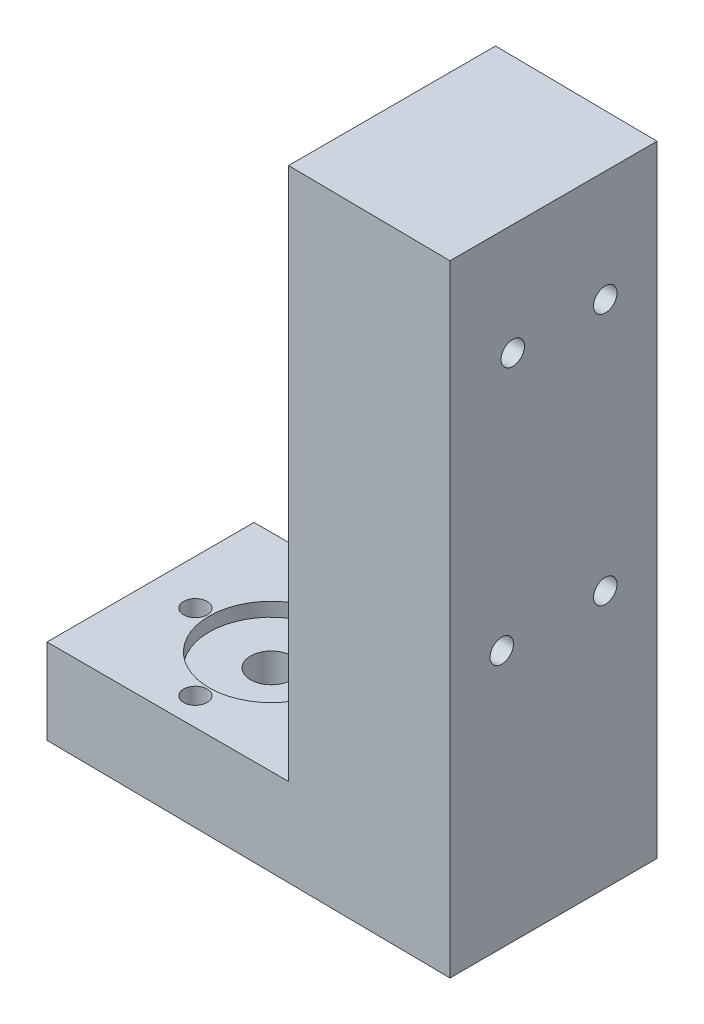
SolidWorks part; units mm, degrees
ref_plane "Front Plane" through (0, 0, 0) normal (0, 0, 1) x (1, 0, 0)
ref_plane "Top Plane" through (0, 0, 0) normal (0, 1, 0) x (1, 0, 0)
ref_plane "Right Plane" through (0, 0, 0) normal (1, 0, 0) x (0, 0, -1)
sketch "Sketch1" plane through (0, 0, 0) normal (0, 0, 1) x (1, 0, 0)
  line L0 (0, 0) -> (58.3993, -0.6295)
  line L1 (58.3993, -0.6295) -> (58.3993, 89.3705)
  line L2 (58.3993, 89.3705) -> (35, 89.6228)
  line L3 (35, 89.6228) -> (35, 12.3346)
  line L4 (35, 12.3346) -> (0, 12.3346)
  line L5 (0, 12.3346) -> (0, 0)
  dimension "D1" = 12.3346
  dimension "D3" = 35
  dimension "D2" = 23.3993
  dimension "D4" = 90
extrude "Boss-Extrude1" add sketch "Sketch1" along normal blind 30
ref_point "Point1"
sketch "Sketch2" plane through (0, 12.3346, 0) normal (0, 1, 0) x (1, 0, 0)
  circle A0 centre (17.5, -15) radius 3
  circle A1 centre (17.5, -15) radius 11
  circle A2 centre (6.5, -15) radius 1.7
  circle A3 centre (17.5, -4) radius 1.7
  circle A4 centre (28.5, -15) radius 1.7
  circle A5 centre (17.5, -26) radius 1.7
extrude "Cut-Extrude1" cut sketch "Sketch2" against normal up to next contours A4 | A3 | A2 | A0 | A5
sketch "Sketch3" plane through (0, 12.3346, 0) normal (0, 1, 0) x (1, 0, 0)
  circle A0 centre (17.5, -15) radius 9
extrude "Cut-Extrude2" cut sketch "Sketch3" against normal blind 2
sketch "Sketch4" plane through (35, 0, 0) normal (-1, 0, 0) x (0, 0, 1)
  line L0 (30, -0.6295) -> (0, -0.6295) construction
  line L1 (30, 89.6228) -> (30, 12.3346) construction
  line L2 (0, 89.6228) -> (0, 12.3346) construction
  circle A0 centre (22.5, 36.7005) radius 1.7
  circle A1 centre (7.5, 36.7005) radius 1.7
  circle A2 centre (7.5, 73.2705) radius 1.7
  circle A3 centre (20.9053, 73.2705) radius 1.7
  point P14 (0, 0)
  point P17 (0, 0)
  dimension "D1" = 37.33
  dimension "D2" = 7.5
  dimension "D3" = 7.5
  dimension "D4" = 73.9
extrude "Cut-Extrude3" cut sketch "Sketch4" against normal up to next
equation "\"b\" = 30'Base"
equation "\"L_1\"= 35'Feature 1 Length"
equation "\"L_2\"= 18'Motor Shaft Length"
equation "\"Yield\"= 45.2'PLA Yield Strength"
equation "\"allow\" = \"Yield\" / \"SF\"'Allowable Stress"
equation "\"SF\"= 3'Safety Factor"
equation "\"E\" = 2.35 * ( 10 ^ 6 )'PLA Modulus of Elasticity"
equation "\"P\"= 300'Force"
equation "\"M_1\" = \"P\" * \"L_2\"'Feature 1 Moment"
equation "\"h_1\"= ( ( ( 6 * \"M_1\" * ( \"L_1\" ^ 2 ) ) / ( ( \"E\" ) * ( \"b\" ) * \"def\" ) ) ) ^ ( 1 / 3 )'Feature 1 Height"
equation "\"def\"= 0.0003'Given Max Deflection"
equation "\"A_1\"= \"b\" * \"h_1\"'Feature 1 Area"
equation "\"L_m\"= 74.6'Motor Body Length"
equation "\"L_3\"= 90'Feature 2 Length"
equation "\"M_2\"= ( \"L_3\" + \"L_2\" ) * \"P\"'Feature 2 Moment"
equation "\"L_f\"= \"h_1\" + 25'Feature 2 Free Length"
equation "\"h_2\"= ( ( 6 * \"M_2\" * ( \"L_f\" ^ 2 ) ) / ( \"E\" * \"b\" * \"def\" ) ) ^ ( 1 / 3 )'Feature 2 Height"
equation "\"A_2\"= \"b\" * \"h_2\"'Feature 2 Area"
equation "\"D1@Sketch1\"=\"h_1\""
equation "\"D3@Sketch1\"=\"L_1\""
equation "\"D2@Sketch1\"=\"h_2\""
equation "\"D4@Sketch1\"=\"L_3\""
equation "\"D1@Boss-Extrude1\"=\"b\""
